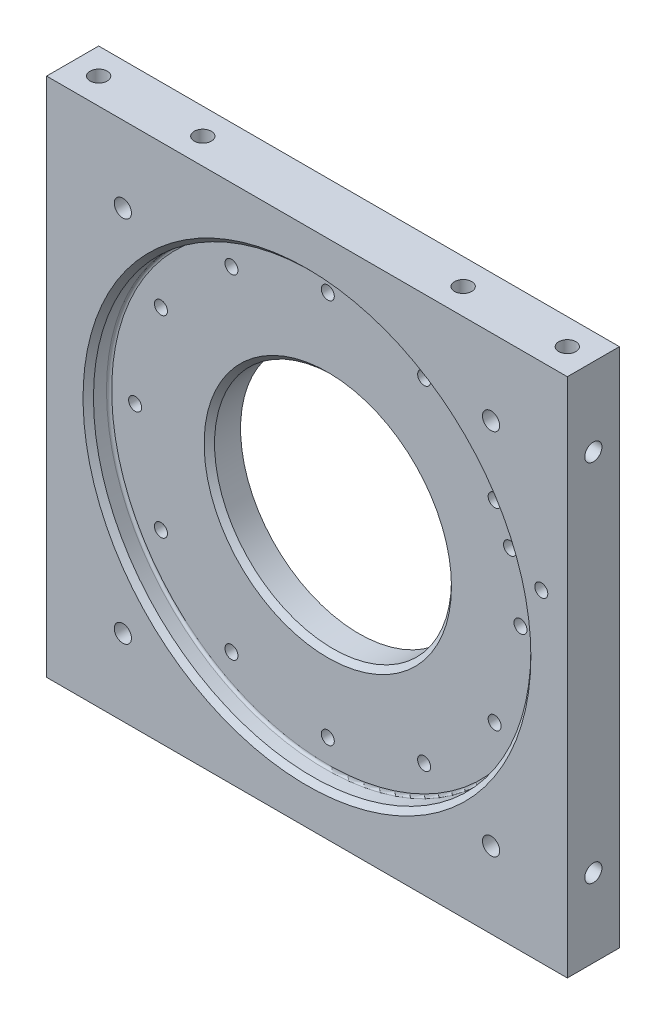
SolidWorks part; units mm, degrees
material "ALUMINIUM,  6082-T6"
ref_plane "Front Plane" through (0, 0, 0) normal (0, 0, 1) x (1, 0, 0)
ref_plane "Top Plane" through (0, 0, 0) normal (0, 1, 0) x (1, 0, 0)
ref_plane "Right Plane" through (0, 0, 0) normal (1, 0, 0) x (0, 0, -1)
sketch "Sketch1" plane through (0, 0, 0) normal (1, 0, 0) x (0, 0, -1)
  line L0 (-5, 50) -> (-5, -50)
  line L2 (-5, -50) -> (5, -50)
  line L8 (5, -50) -> (5, 50)
  line L9 (5, 50) -> (-5, 50)
  line L10 (-5, 50) -> (5, -50) construction
  dimension "D1" = 100
  dimension "D2" = 10
extrude "Boss-Extrude1" add sketch "Sketch1" along normal mid plane 100
sketch "Sketch2" plane through (0, 0, 5) normal (0, 0, 1) x (1, 0, 0)
  circle A0 centre (0, 0) radius 42
  dimension "D1" = 84
extrude "Cut-Extrude1" cut sketch "Sketch2" against normal blind 4
sketch "Sketch4" plane through (0, 0, 1) normal (0, 0, 1) x (1, 0, 0)
  circle A0 centre (0, 0) radius 22.75
  dimension "D1" = 45.5
extrude "Cut-Extrude3" cut sketch "Sketch4" against normal up to next
hole_wizard "M3 Tapped Hole1" positions "Sketch9" profile "Sketch10" tap size "M3" standard "ISO" end condition through all
sketch "Sketch9" plane through (0, 0, -5) normal (0, 0, 1) x (1, 0, 0)
  line L4 (-37, 0) -> (37, 0) construction
  line L5 (18.5, 32.0429) -> (-18.5, -32.0429) construction
  line L6 (-32.0429, 18.5) -> (32.0429, -18.5) construction
  line L7 (0, 37) -> (0, -37) construction
  line L8 (-18.5, 32.0429) -> (18.5, -32.0429) construction
  line L11 (-32.0429, -18.5) -> (32.0429, 18.5) construction
  circle A2 centre (0, 0) radius 37 construction
  circle A4 centre (0, 0) radius 22.75 construction
  point P28 (-37, 0)
  point P29 (37, 0)
  point P30 (18.5, 32.0429)
  point P31 (-32.0429, 18.5)
  point P32 (32.0429, -18.5)
  point P33 (-18.5, -32.0429)
  point P40 (0, 37)
  point P41 (0, -37)
  point P49 (-18.5, 32.0429)
  point P51 (18.5, -32.0429)
  point P53 (32.0429, 18.5)
  point P55 (-32.0429, -18.5)
  point P65 (45, 12)
  point P68 (35, 12)
  point P73 (0, 0)
  point P74 (0, 0)
  dimension "D1" = 30
  dimension "D3" = 74
  dimension "D7" = 35
  dimension "D8" = 12
  dimension "D2" = 30
  dimension "D4" = 30
  dimension "D5" = 30
  dimension "D6" = 10
cosmetic thread "Hole Thread59" parameters "D2"=3
sketch "Sketch10" plane through (35, 12, -5) normal (1, 0, 0) x (0, 1, 0)
  line L0 (0, 0) -> (0, 10)
  line L1 (0, 10) -> (1.25, 10)
  line L2 (1.25, 10) -> (1.25, 0)
  line L5 (1.25, 0) -> (0, 0)
  line L11 (0, -6.35) -> (0, 107.95) construction
  dimension "Thru Tap Drill Dia." = 2.5
  dimension "Thru Tap Drill Depth" = 10
cosmetic thread "Hole Thread60" parameters "D2"=3
cosmetic thread "Hole Thread61" parameters "D2"=3
cosmetic thread "Hole Thread62" parameters "D2"=3
cosmetic thread "Hole Thread63" parameters "D2"=3
cosmetic thread "Hole Thread64" parameters "D2"=3
cosmetic thread "Hole Thread65" parameters "D2"=3
cosmetic thread "Hole Thread66" parameters "D2"=3
cosmetic thread "Hole Thread67" parameters "D2"=3
cosmetic thread "Hole Thread68" parameters "D2"=3
cosmetic thread "Hole Thread69" parameters "D2"=3
cosmetic thread "Hole Thread70" parameters "D2"=3
cosmetic thread "Hole Thread71" parameters "D2"=3
cosmetic thread "Hole Thread72" parameters "D2"=3
fillet "Fillet3" radius 0.5 1 edges at (42, 0, 1)
chamfer "Chamfer1" distance 1 angle 45 2 edges at (22.75, 0, 1) (42, 0, 5)
hole_wizard "M4 Tapped Hole1" positions "Sketch11" profile "Sketch12" tap size "M4" standard "ISO"
sketch "Sketch11" plane through (0, 50, 0) normal (0, 1, 0) x (1, 0, 0)
  line L0 (-45, 0) -> (-25, 0) construction
  line L1 (-25, 0) -> (25, 0) construction
  line L2 (25, 0) -> (45, 0) construction
  line L4 (-50, 5) -> (-50, -5) construction
  point P0 (-45, 0)
  point P3 (-25, 0)
  point P6 (25, 0)
  point P9 (45, 0)
  dimension "D1" = 20
  dimension "D2" = 5
sketch "Sketch12" plane through (-45, 50, 0) normal (1, 0, 0) x (0, 0, 1)
  line L0 (0, 0) -> (0, 11.9914)
  line L1 (0, 11.9914) -> (1.65, 11)
  line L2 (1.65, 11) -> (1.65, 0)
  line L5 (1.65, 0) -> (0, 0)
  line L10 (0, 11.9914) -> (-1.65, 11) construction
  line L11 (0, -6.35) -> (0, 107.95) construction
  dimension "Tap Drill Dia." = 3.3
  dimension "Tap Drill Depth" = 11
  dimension "Drill Angle" = 118
cosmetic thread "Hole Thread42" parameters "D1"=8, "D2"=4
cosmetic thread "Hole Thread43" parameters "D1"=8, "D2"=4
cosmetic thread "Hole Thread44" parameters "D1"=8, "D2"=4
cosmetic thread "Hole Thread45" parameters "D1"=8, "D2"=4
hole_wizard "M4 Tapped Hole2" positions "Sketch13" profile "Sketch14" tap size "M4" standard "ISO"
sketch "Sketch13" plane through (0, -50, 0) normal (0, -1, 0) x (-1, 0, 0)
  point P0 (45, 0)
  point P3 (25, 0)
  point P6 (-25, 0)
  point P9 (-45, 0)
sketch "Sketch14" plane through (-45, -50, 0) normal (1, 0, 0) x (0, 0, -1)
  line L0 (0, 0) -> (0, 11.9914)
  line L1 (0, 11.9914) -> (1.65, 11)
  line L2 (1.65, 11) -> (1.65, 0)
  line L5 (1.65, 0) -> (0, 0)
  line L10 (0, 11.9914) -> (-1.65, 11) construction
  line L11 (0, -6.35) -> (0, 107.95) construction
  dimension "Tap Drill Dia." = 3.3
  dimension "Tap Drill Depth" = 11
  dimension "Drill Angle" = 118
cosmetic thread "Hole Thread46" parameters "D1"=8, "D2"=4
cosmetic thread "Hole Thread47" parameters "D1"=8, "D2"=4
cosmetic thread "Hole Thread48" parameters "D1"=8, "D2"=4
cosmetic thread "Hole Thread49" parameters "D1"=8, "D2"=4
hole_wizard "M4 Tapped Hole3" positions "Sketch15" profile "Sketch16" tap size "M4" standard "ISO"
sketch "Sketch15" plane through (50, 0, 0) normal (1, 0, 0) x (0, 0, -1)
  line L0 (0, -35) -> (0, 35) construction
  point P0 (0, 35)
  point P3 (0, -35)
  dimension "D1" = 70
sketch "Sketch16" plane through (50, 35, 0) normal (0, 1, 0) x (0, 0, -1)
  line L0 (0, 0) -> (0, 11.9914)
  line L1 (0, 11.9914) -> (1.65, 11)
  line L2 (1.65, 11) -> (1.65, 0)
  line L5 (1.65, 0) -> (0, 0)
  line L10 (0, 11.9914) -> (-1.65, 11) construction
  line L11 (0, -6.35) -> (0, 107.95) construction
  dimension "Tap Drill Dia." = 3.3
  dimension "Tap Drill Depth" = 11
  dimension "Drill Angle" = 118
cosmetic thread "Hole Thread50" parameters "D1"=8, "D2"=4
cosmetic thread "Hole Thread51" parameters "D1"=8, "D2"=4
hole_wizard "M4 Tapped Hole4" positions "Sketch17" profile "Sketch18" tap size "M4" standard "ISO"
sketch "Sketch17" plane through (-50, 0, 0) normal (-1, 0, 0) x (0, 0, 1)
  point P0 (0, 35)
  point P3 (0, -35)
sketch "Sketch18" plane through (-50, 35, 0) normal (0, 1, 0) x (0, 0, 1)
  line L0 (0, 0) -> (0, 11.9914)
  line L1 (0, 11.9914) -> (1.65, 11)
  line L2 (1.65, 11) -> (1.65, 0)
  line L5 (1.65, 0) -> (0, 0)
  line L10 (0, 11.9914) -> (-1.65, 11) construction
  line L11 (0, -6.35) -> (0, 107.95) construction
  dimension "Tap Drill Dia." = 3.3
  dimension "Tap Drill Depth" = 11
  dimension "Drill Angle" = 118
cosmetic thread "Hole Thread52" parameters "D1"=8, "D2"=4
cosmetic thread "Hole Thread53" parameters "D1"=8, "D2"=4
hole_wizard "M4 Tapped Hole5" positions "Sketch19" profile "Sketch20" tap size "M4" standard "ISO" end condition up to next
sketch "Sketch19" plane through (0, 0, 5) normal (0, 0, 1) x (1, 0, 0)
  line L0 (-35.3553, 35.3553) -> (35.3553, -35.3553) construction
  line L3 (35.3553, 35.3553) -> (-35.3553, -35.3553) construction
  point P1 (-35.3553, 35.3553)
  point P2 (35.3553, -35.3553)
  point P6 (35.3553, 35.3553)
  point P7 (-35.3553, -35.3553)
  point P10 (0, 0)
  dimension "D1" = 100
sketch "Sketch20" plane through (-35.3553, 35.3553, 5) normal (1, 0, 0) x (0, -1, 0)
  line L0 (0, 0) -> (0, 10)
  line L1 (0, 10) -> (1.65, 10)
  line L2 (1.65, 10) -> (1.65, 0)
  line L5 (1.65, 0) -> (0, 0)
  line L11 (0, -6.35) -> (0, 107.95) construction
  dimension "Thru Tap Drill Dia." = 3.3
  dimension "Thru Tap Drill Depth" = 10
cosmetic thread "Hole Thread54" parameters "D2"=4
cosmetic thread "Hole Thread55" parameters "D2"=4
cosmetic thread "Hole Thread56" parameters "D2"=4
cosmetic thread "Hole Thread57" parameters "D2"=4
